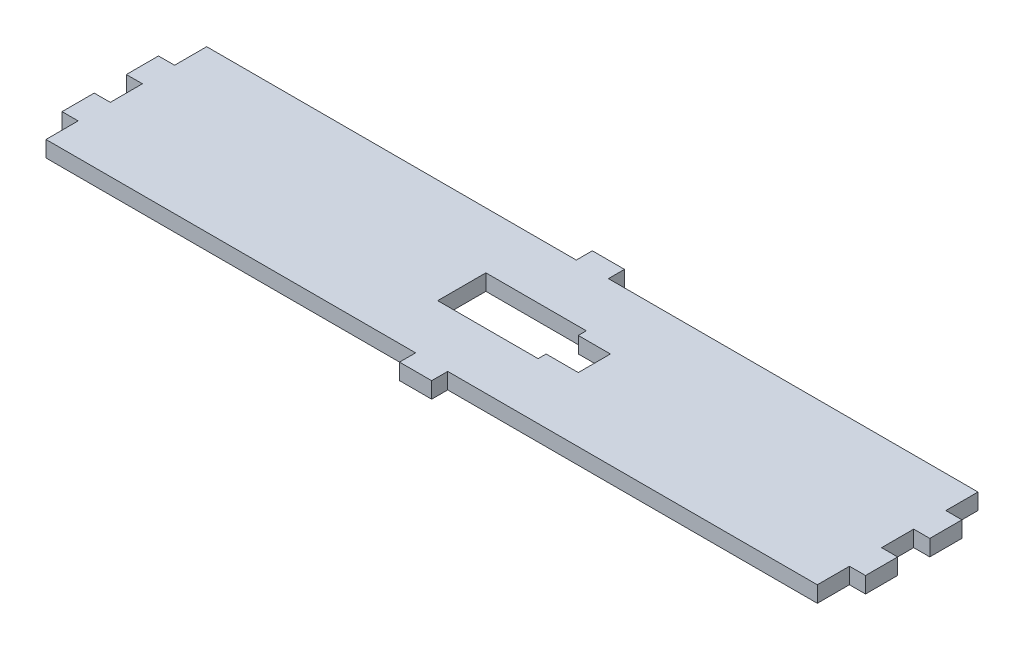
SolidWorks part; units mm, degrees
material "Mahogany"
ref_plane "Front" through (0, 0, 0) normal (0, 0, 1) x (1, 0, 0)
ref_plane "Top" through (0, 0, 0) normal (0, 1, 0) x (1, 0, 0)
ref_plane "Right" through (0, 0, 0) normal (1, 0, 0) x (0, 0, -1)
sketch "Sketch1" plane through (0, 0, 0) normal (0, 1, 0) x (1, 0, 0)
  line L0 (311.15, 25.4) -> (311.15, 38.1) construction
  line L1 (0, 0) -> (304.8, 0)
  line L2 (0, 0) -> (0, 63.5)
  line L3 (0, 63.5) -> (304.8, 63.5)
  line L4 (304.8, 0) -> (304.8, 63.5)
  line L5 (304.8, 50.8) -> (311.15, 50.8)
  line L6 (304.8, 50.8) -> (304.8, 38.1)
  line L7 (304.8, 38.1) -> (311.15, 38.1)
  line L8 (311.15, 50.8) -> (311.15, 38.1)
  line L9 (304.8, 25.4) -> (311.15, 25.4)
  line L10 (304.8, 25.4) -> (304.8, 12.7)
  line L11 (304.8, 12.7) -> (311.15, 12.7)
  line L12 (311.15, 25.4) -> (311.15, 12.7)
  line L13 (152.4, 63.5) -> (152.4, 0) construction
  line L14 (-6.35, 25.4) -> (-6.35, 38.1) construction
  line L15 (132.5563, 41.275) -> (172.2438, 41.275)
  line L16 (132.5563, 41.275) -> (132.5563, 22.225)
  line L17 (132.5563, 22.225) -> (172.2438, 22.225)
  line L18 (172.2438, 41.275) -> (172.2438, 22.225)
  line L19 (-6.35, 25.4) -> (-6.35, 12.7)
  line L20 (0, 12.7) -> (-6.35, 12.7)
  line L21 (0, 25.4) -> (0, 12.7)
  line L22 (0, 25.4) -> (-6.35, 25.4)
  line L23 (-6.35, 50.8) -> (-6.35, 38.1)
  line L24 (0, 38.1) -> (-6.35, 38.1)
  line L25 (0, 50.8) -> (0, 38.1)
  line L26 (0, 50.8) -> (-6.35, 50.8)
  line L27 (132.5563, 31.75) -> (172.2438, 31.75) construction
  line L28 (172.2438, 38.1) -> (184.9438, 38.1)
  line L29 (172.2438, 38.1) -> (172.2438, 25.4)
  line L30 (172.2438, 25.4) -> (184.9438, 25.4)
  line L31 (184.9438, 38.1) -> (184.9438, 25.4)
  line L32 (146.05, 0) -> (158.75, 0)
  line L33 (146.05, 0) -> (146.05, -6.35)
  line L34 (146.05, -6.35) -> (158.75, -6.35)
  line L35 (158.75, 0) -> (158.75, -6.35)
  line L36 (158.75, 63.5) -> (158.75, 69.85)
  line L37 (146.05, 69.85) -> (158.75, 69.85)
  line L38 (146.05, 63.5) -> (146.05, 69.85)
  line L39 (146.05, 63.5) -> (158.75, 63.5)
  point P13 (311.15, 31.75)
  point P14 (304.8, 31.75)
  point P21 (152.4, 41.275)
  point P22 (132.5563, 31.75)
  point P23 (0, 31.75)
  point P36 (184.9438, 31.75)
  point P37 (172.2438, 31.75)
  point P42 (152.4, -6.35)
  point P43 (152.4, 22.225)
  dimension "D1" = 63.5
  dimension "D2" = 304.8
  dimension "D3" = 6.35
  dimension "D4" = 19.05
  dimension "D5" = 12.7
  dimension "D6" = 39.6875
  dimension "D7" = 12.7
  dimension "D8" = 12.7
  dimension "D9" = 12.7
  dimension "D10" = 6.35
extrude "Boss-Extrude1" add sketch "Sketch1" along normal blind 6.35 contours L1 L4 L3 L2 L15 L18 L17 L16 | L8 L5 L4 L7 | L12 L9 L4 L11 | L2 L22 L19 L20 | L2 L26 L23 L24 | L35 L1 L33 L34 | L38 L3 L36 L37
